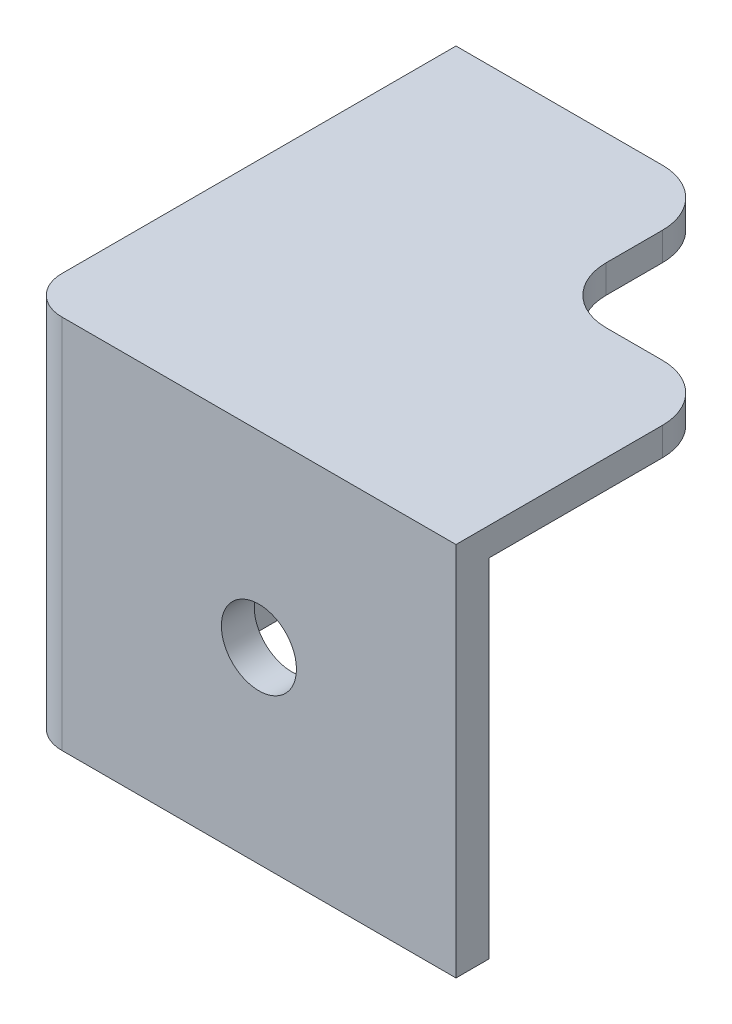
SolidWorks part; units mm, degrees
ref_plane "Alzado" through (0, 0, 0) normal (0, 0, 1) x (1, 0, 0)
ref_plane "Planta" through (0, 0, 0) normal (0, 1, 0) x (1, 0, 0)
ref_plane "Vista lateral" through (0, 0, 0) normal (1, 0, 0) x (0, 0, -1)
sketch "Croquis1" plane through (0, 0, 0) normal (0, 1, 0) x (1, 0, 0)
  line L0 (0, 0) -> (23, 0)
  line L1 (23, 0) -> (23, 14)
  line L2 (23, 14) -> (14, 14)
  line L3 (14, 14) -> (14, 23)
  line L4 (14, 23) -> (0, 23)
  line L5 (0, 23) -> (0, 0)
  point P3 (0, 0)
  dimension "D1" = 23
  dimension "D2" = 23
  dimension "D3" = 14
  dimension "D4" = 14
extrude "Saliente-Extruir1" add sketch "Croquis1" along normal blind 20
sketch "Croquis2" plane through (0, 0, 0) normal (0, -1, 0) x (1, 0, 0)
  line L0 (1.75, -23) -> (1.75, -1.75)
  line L1 (14, -23) -> (0, -23) construction
  line L2 (1.75, -1.75) -> (23, -1.75)
  line L3 (23, 0) -> (23, -14) construction
  line L4 (23, -1.75) -> (23, -14)
  line L5 (23, -14) -> (14, -14)
  line L6 (14, -14) -> (14, -23)
  line L7 (14, -23) -> (1.75, -23)
  line L8 (0, -23) -> (0, 0) construction
  line L9 (0, 0) -> (23, 0) construction
  dimension "D1" = 1.75
  dimension "D2" = 1.75
extrude "Cortar-Extruir1" cut sketch "Croquis2" against normal blind 18.5
fillet "Redondeo1" radius 2 2 edges at (0, 10, 0) (1.75, 9.25, -1.75)
fillet "Redondeo2" radius 3 3 edges at (14, 19.25, -23) (23, 19.25, -14) (14, 19.25, -14)
sketch "Croquis3" plane through (0, 0, 0) normal (-1, 0, 0) x (0, 0, 1)
  line L0 (-12.5, 0) -> (-12.5, 20) construction
  line L1 (-23, 0) -> (-2, 0) construction
  line L2 (-23, 20) -> (-2, 20) construction
  line L3 (-23, 10) -> (-2, 10) construction
  line L4 (-23, 20) -> (-23, 0) construction
  line L5 (-2, 0) -> (-2, 20) construction
  circle A0 centre (-12.5, 10) radius 2
  dimension "D1" = 4
extrude "Cortar-Extruir2" cut sketch "Croquis3" against normal blind 18.5
sketch "Croquis4" plane through (0, 0, 0) normal (0, 0, 1) x (1, 0, 0)
  line L0 (12.5, 20) -> (12.5, 0) construction
  line L1 (2, 20) -> (23, 20) construction
  line L2 (2, 0) -> (23, 0) construction
  line L3 (23, 10) -> (2, 10) construction
  line L4 (23, 20) -> (23, 0) construction
  line L5 (2, 20) -> (2, 0) construction
  circle A0 centre (12.5, 10) radius 2
  dimension "D1" = 4
extrude "Cortar-Extruir3" cut sketch "Croquis4" against normal blind 18.5
